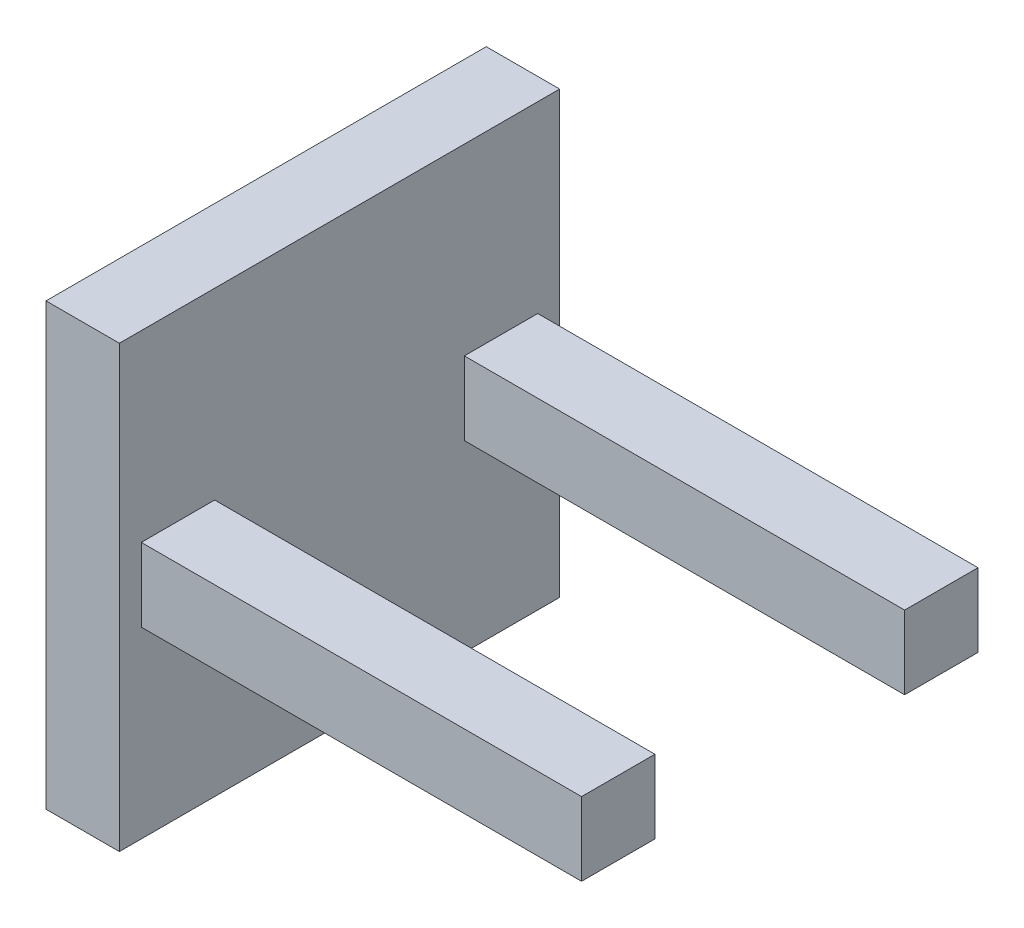
SolidWorks part; units mm, degrees
ref_plane "Front Plane" through (0, 0, 0) normal (0, 0, 1) x (1, 0, 0)
ref_plane "Top Plane" through (0, 0, 0) normal (0, 1, 0) x (1, 0, 0)
ref_plane "Right Plane" through (0, 0, 0) normal (1, 0, 0) x (0, 0, -1)
sketch "Sketch1" plane through (0, 0, 0) normal (1, 0, 0) x (0, 0, -1)
  line L1 (-15, 15) -> (15, 15)
  line L2 (-15, 15) -> (-15, -15)
  line L3 (-15, -15) -> (15, -15)
  line L4 (15, 15) -> (15, -15)
  line L5 (-15, 15) -> (15, -15) construction
  line L6 (-15, -15) -> (15, 15) construction
  point P0 (0, 0)
  dimension "D1" = 30
  dimension "D2" = 30
extrude "Boss-Extrude1" add sketch "Sketch1" along normal blind 5
ref_plane "Plane1" through (0, 0, 0) normal (0, 1, 0) x (1, 0, 0)
sketch "Sketch2" plane through (0, 0, 0) normal (0, 1, 0) x (1, 0, 0)
  line L0 (5, 15) -> (5, -15) construction
  line L1 (5, 13.5071) -> (35, 13.5071)
  line L2 (5, 13.5071) -> (5, 8.5071)
  line L3 (5, 8.5071) -> (35, 8.5071)
  line L4 (35, 13.5071) -> (35, 8.5071)
  line L5 (5, 0) -> (50005, 0) construction
  line L6 (5, -8.5071) -> (35, -8.5071)
  line L7 (35, -13.5071) -> (35, -8.5071)
  line L8 (5, -13.5071) -> (35, -13.5071)
  line L9 (5, -13.5071) -> (5, -8.5071)
  point P8 (5, 0)
  dimension "D1" = 30
  dimension "D2" = 5
extrude "Boss-Extrude2" add sketch "Sketch2" along normal mid plane 5
